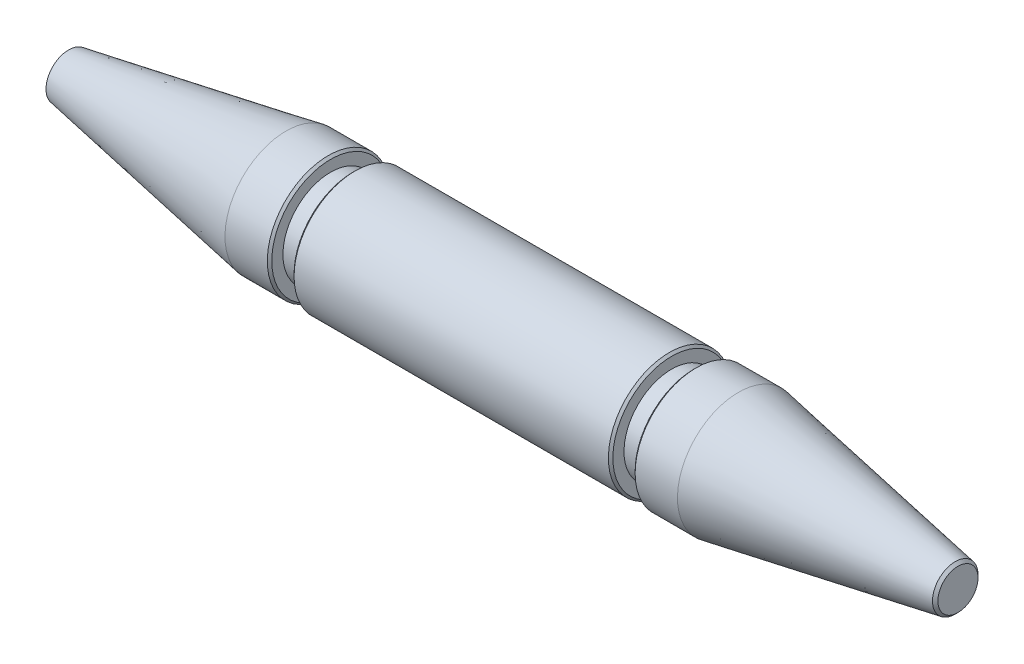
SolidWorks part; units mm, degrees
ref_plane "前视基准面" through (0, 0, 0) normal (0, 0, 1) x (1, 0, 0)
ref_plane "上视基准面" through (0, 0, 0) normal (0, 1, 0) x (1, 0, 0)
ref_plane "右视基准面" through (0, 0, 0) normal (1, 0, 0) x (0, 0, -1)
sketch "草图1" plane through (0, 0, 0) normal (0, 0, 1) x (1, 0, 0)
  line L0 (-100, 0) -> (100, 0)
  line L1 (-100, 0) -> (-100, 5)
  line L2 (-100, 5) -> (-50.7596, 13.6824)
  line L3 (-50.7596, 13.6824) -> (-40.7596, 13.6824)
  line L4 (-40.7596, 13.6824) -> (-40.7596, 10.6824)
  line L5 (-40.7596, 10.6824) -> (-35.7596, 10.6824)
  line L6 (-35.7596, 10.6824) -> (-35.7596, 13.6824)
  line L7 (-35.7596, 13.6824) -> (35.7596, 13.6824)
  line L8 (0, 0) -> (0, 13.6824) construction
  line L9 (100, 0) -> (100, 5)
  line L10 (35.7596, 10.6824) -> (35.7596, 13.6824)
  line L11 (40.7596, 10.6824) -> (35.7596, 10.6824)
  line L12 (40.7596, 13.6824) -> (40.7596, 10.6824)
  line L13 (50.7596, 13.6824) -> (40.7596, 13.6824)
  line L14 (100, 5) -> (50.7596, 13.6824)
  point P4 (0, 0)
  dimension "D1" = 200
  dimension "D2" = 5
  dimension "D3" = 50
  dimension "D4" = 10
  dimension "D5" = 49.2404
  dimension "D6" = 10
  dimension "D7" = 3
  dimension "D8" = 5
  dimension "D9" = 13.6824
revolve "旋转1" add sketch "草图1" angle 360 about L0
chamfer "倒角1" distance 0.5 angle 45 6 edges at (-35.7596, -13.6824, 0) (-40.7596, -13.6824, 0) (35.7596, -13.6824, 0) (40.7596, -13.6824, 0) (-100, -5, 0) (100, -5, 0)
